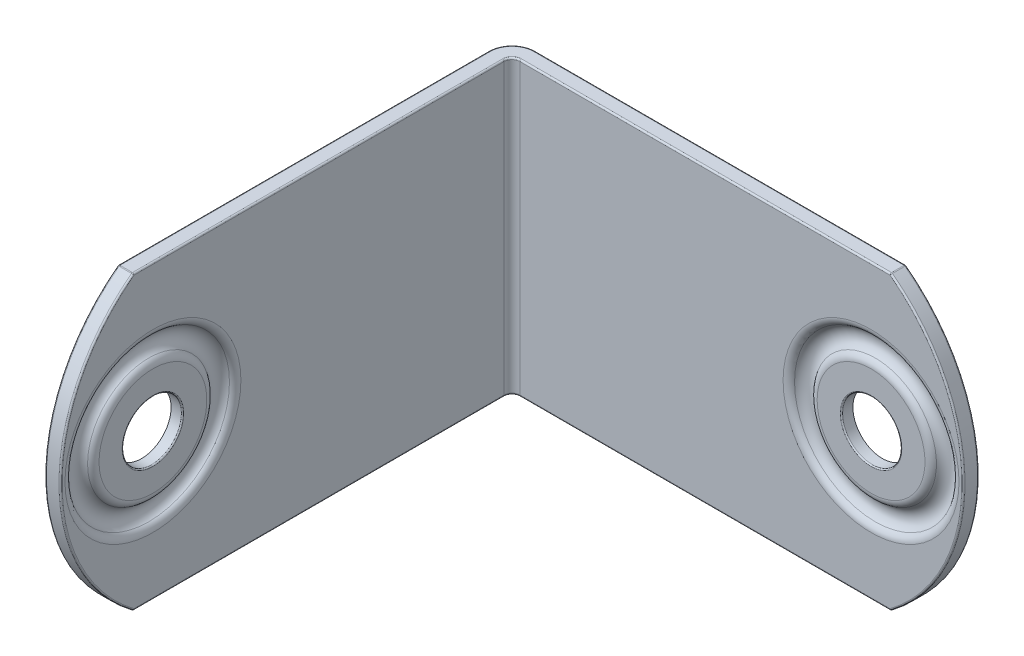
SolidWorks part; units mm, degrees
ref_plane "Front Plane" through (0, 0, 0) normal (0, 0, 1) x (1, 0, 0)
ref_plane "Top Plane" through (0, 0, 0) normal (0, 1, 0) x (1, 0, 0)
ref_plane "Right Plane" through (0, 0, 0) normal (1, 0, 0) x (0, 0, -1)
sketch "Sketch1" plane through (0, 0, 0) normal (0, 1, 0) x (1, 0, 0)
  line L0 (-19.05, -19.05) -> (-19.05, 19.05)
  line L1 (-19.05, 19.05) -> (19.05, 19.05)
  line L2 (-19.05, -19.05) -> (-17.78, -19.05)
  line L3 (-17.78, -19.05) -> (-17.78, 17.78)
  line L4 (-17.78, 17.78) -> (19.05, 17.78)
  line L5 (19.05, 17.78) -> (19.05, 19.05)
  line L6 (11.5094, 19.05) -> (11.5094, 17.78) construction
  line L7 (-19.05, -11.5094) -> (-17.78, -11.5094) construction
  line L8 (13.9224, 19.05) -> (13.9224, 17.78)
  line L9 (-19.05, -9.0964) -> (-17.78, -9.0964)
  line L10 (-19.05, -13.9224) -> (-17.78, -13.9224)
  line L11 (9.0964, 19.05) -> (9.0964, 17.78)
  arc A0 (-19.05, 17.145) -> (-17.145, 19.05) centre (-17.145, 17.145) cw
  arc A1 (-17.78, 17.145) -> (-17.145, 17.78) centre (-17.145, 17.145) cw
  point P2 (-19.05, 0)
  point P5 (0, 19.05)
  point P27 (-17.78, -13.9224)
  point P29 (9.0964, 17.78)
  dimension "D1" = 0.635
  dimension "Length (B)" = 38.1
  dimension "Length (A)" = 38.1
  dimension "Thickness" = 1.27
  dimension "Mounting Hole Location 2" = 7.5406
  dimension "Mounting Hole Location 1" = 7.5406
  dimension "Mounting Hole Diameter 2" = 4.826
  dimension "Mounting Hole Diameter 1" = 4.826
sketch "Sketch2" plane through (0, 0, 0) normal (1, 0, 0) x (0, 0, -1)
  line L0 (0, 11.9062) -> (0, -11.9062)
  arc A0 (-13.0969, 11.9062) -> (-13.0969, -11.9062) centre (-4.1672, 0) ccw
  point P2 (0, 0)
  point P10 (-19.05, 0)
  dimension "Length (C)" = 23.8125
  dimension "D1" = 5.9531
sketch "Sketch3" plane through (0, 0, 0) normal (0, 1, 0) x (1, 0, 0)
  line L0 (-19.05, -19.05) -> (-17.78, -19.05) construction
  line L1 (-17.78, -19.05) -> (-17.78, 17.78) construction
  line L2 (-17.78, 17.78) -> (19.05, 17.78) construction
  line L3 (19.05, 17.78) -> (19.05, 19.05) construction
  line L4 (-19.05, 19.05) -> (19.05, 19.05) construction
  line L5 (-19.05, -19.05) -> (-19.05, 19.05) construction
  line L6 (-19.05, -19.05) -> (-17.78, -19.05)
  line L7 (-17.78, -19.05) -> (-17.78, 17.145)
  line L8 (-17.145, 17.78) -> (19.05, 17.78)
  line L9 (19.05, 17.78) -> (19.05, 19.05)
  line L10 (-17.145, 19.05) -> (19.05, 19.05)
  line L11 (-19.05, -19.05) -> (-19.05, 17.145)
  arc A0 (-17.145, 17.78) -> (-17.78, 17.145) centre (-17.145, 17.145) ccw construction
  arc A1 (-17.145, 19.05) -> (-19.05, 17.145) centre (-17.145, 17.145) ccw construction
  arc A2 (-17.145, 17.78) -> (-17.78, 17.145) centre (-17.145, 17.145) ccw
  arc A3 (-17.145, 19.05) -> (-19.05, 17.145) centre (-17.145, 17.145) ccw
extrude "Boss-Extrude1" add sketch "Sketch3" against normal up to vertex (11.9062 mm away) from vertex at 11.9062 starting at point (0, 11.9062, 0)
sketch "Sketch4" plane through (0, 0, 0) normal (0, 1, 0) x (1, 0, 0)
  line L1 (-19.05, -11.5094) -> (-17.78, -11.5094)
  line L2 (-19.05, -11.5094) -> (-19.05, -9.0964)
  line L3 (-19.05, -9.0964) -> (-17.78, -9.0964)
  line L4 (-17.78, -11.5094) -> (-17.78, -9.0964)
revolve "Cut-Revolve1" cut sketch "Sketch4" angle 360 about L1
sketch "Sketch5" plane through (0, 0, 0) normal (0, 1, 0) x (1, 0, 0)
  line L1 (11.5094, 19.05) -> (13.9224, 19.05)
  line L2 (11.5094, 19.05) -> (11.5094, 17.78)
  line L3 (11.5094, 17.78) -> (13.9224, 17.78)
  line L4 (13.9224, 19.05) -> (13.9224, 17.78)
revolve "Cut-Revolve2" cut sketch "Sketch5" angle 360 about L2
sketch "Sketch6" plane through (-17.78, 0, 0) normal (1, 0, 0) x (0, 0, -1)
  line L0 (-13.0969, 11.9063) -> (-19.05, 11.9062)
  line L1 (-19.05, 11.9062) -> (-19.05, 0)
  line L2 (-19.05, 0) -> (-19.05, -11.9062)
  line L3 (-19.05, -11.9062) -> (-13.0969, -11.9063)
  arc A0 (-13.0969, 11.9063) -> (-13.0969, -11.9063) centre (-4.1672, 0) ccw construction
  arc A1 (-13.0969, 11.9063) -> (-13.0969, -11.9063) centre (-4.1672, 0) ccw
  line M2 (17.145, 11.9062) -> (-19.05, 11.9062)
  line M3 (-19.05, 11.9062) -> (-19.05, -11.9062)
  line M4 (-19.05, -11.9062) -> (17.145, -11.9062)
extrude "Cut-Extrude1" cut sketch "Sketch6" against normal through all contours A1 M2 M3 | A1 M3 M4
sketch "Sketch7" plane through (0, 0, -17.78) normal (0, 0, 1) x (1, 0, 0)
  line L0 (-17.145, 11.9062) -> (19.05, 11.9062) construction
  line L1 (-17.145, -11.9062) -> (19.05, -11.9062) construction
  line L3 (13.0969, 11.9062) -> (19.05, 11.9062)
  line L4 (19.05, 11.9062) -> (19.05, 0)
  line L5 (19.05, 0) -> (19.05, -11.9062)
  line L6 (19.05, -11.9062) -> (13.0969, -11.9062)
  arc A0 (13.0969, 11.9062) -> (13.0969, -11.9062) centre (4.1672, 0) cw
  line M2 (19.05, 11.9062) -> (-17.145, 11.9062)
  line M4 (-17.145, -11.9062) -> (19.05, -11.9062)
  line M5 (19.05, -11.9062) -> (19.05, 11.9062)
  dimension "D1" = 5.9531
extrude "Cut-Extrude2" cut sketch "Sketch7" against normal through all contours A0 M2 M5 | A0 M5 M4
fillet "Fillet1" radius 0.127 20 edges at (-19.05, -11.9062, -2.0241) (-18.492, -11.9062, -18.492) (-19.05, 11.9062, -2.0241) (-18.492, 11.9062, -18.492) (-2.0241, -11.9062, -17.78) (-17.594, -11.9062, -17.594) (-2.0241, 11.9062, -17.78) (-17.594, 11.9062, -17.594) (-18.415, -11.9062, 13.0969) (13.0969, -11.9062, -18.415) (13.0969, 11.9062, -18.415) (-18.415, 11.9062, 13.0969) (-2.0241, -11.9062, -19.05) (-2.0241, 11.9062, -19.05) (19.05, 0, -19.05) (19.05, 0, -17.78) (-17.78, -11.9062, -2.0241) (-17.78, 11.9062, -2.0241) (-19.05, 0, 19.05) (-17.78, 0, 19.05)
fillet "Fillet2" radius 0.0965 4 edges at (9.0964, 0, -19.05) (-19.05, 0, 13.9224) (9.0964, 0, -17.78) (-17.78, 0, 13.9224)
sketch "Sketch8" plane through (0, 0, 0) normal (0, 1, 0) x (1, 0, 0)
  line L0 (-17.78, -4.3339) -> (-17.78, -7.112)
  line L1 (-17.78, -19.05) -> (-17.78, 17.78) construction
  line L2 (-19.05, -19.05) -> (-19.05, 19.05) construction
  line L3 (-18.7098, -7.112) -> (-18.7098, -9.0964)
  line L4 (-17.78, -7.112) -> (-17.78, -8.9999) construction
  line L6 (-18.7098, -9.0964) -> (-19.05, -9.0964)
  line L8 (-19.05, -9.0964) -> (-17.78, -9.0964) construction
  line L9 (-19.05, -9.0964) -> (-19.05, -6.5167)
  arc A0 (-17.78, -7.112) -> (-18.1202, -6.5167) centre (-18.471, -7.112) ccw
  arc A1 (-18.1202, -6.5167) -> (-18.1202, -4.9292) centre (-17.6524, -5.7229) cw
  arc A2 (-18.1202, -4.9292) -> (-17.78, -4.3339) centre (-18.471, -4.3339) ccw
  arc A3 (-18.7098, -7.112) -> (-19.05, -6.5167) centre (-19.4008, -7.112) ccw
  arc A4 (-19.05, -6.5167) -> (-19.05, -4.9292) centre (-18.5823, -5.7229) cw construction
  arc A5 (-19.05, -4.9292) -> (-18.7098, -4.3339) centre (-19.4008, -4.3339) ccw construction
  point P21 (-19.5036, -5.7229)
  point P22 (-18.5738, -5.7229)
  dimension "D1" = 0.7937
  dimension "D2" = 1.9844
  dimension "D3" = 2.7781
  dimension "D4" = 0.7937
  dimension "D5" = 1.5875
revolve "Cut-Revolve3" cut sketch "Sketch8" angle 360 about L7
sketch "Sketch9" plane through (0, 0, 0) normal (0, 1, 0) x (1, 0, 0)
  line L0 (-19.05, -4.9292) -> (-19.05, -6.5167)
  arc A0 (-19.05, -4.9292) -> (-19.05, -6.5167) centre (-18.5823, -5.7229) ccw construction
  arc A1 (-19.05, -4.9292) -> (-19.05, -6.5167) centre (-18.5823, -5.7229) ccw
revolve "Revolve1" add sketch "Sketch9" angle 360 about L7
sketch "Sketch10" plane through (0, 0, 0) normal (0, 1, 0) x (1, 0, 0)
  line L0 (18.6849, 17.78) -> (15.9068, 17.78)
  line L1 (15.9068, 18.7098) -> (13.9224, 18.7098)
  line L2 (15.9068, 17.78) -> (13.9224, 17.78) construction
  line L3 (13.9224, 18.7098) -> (13.9224, 19.05)
  line L4 (13.9224, 19.05) -> (16.5021, 19.05)
  line L5 (-19.05, 19.05) -> (19.05, 19.05) construction
  line L6 (13.9224, 19.05) -> (13.9224, 17.78) construction
  arc A0 (15.9068, 17.78) -> (16.5021, 18.1202) centre (15.9068, 18.471) ccw
  arc A1 (16.5021, 18.1202) -> (18.0896, 18.1202) centre (17.2958, 17.6524) cw
  arc A2 (18.0896, 18.1202) -> (18.6849, 17.78) centre (18.6849, 18.471) ccw
  arc A3 (15.9068, 18.7098) -> (16.5021, 19.05) centre (15.9068, 19.4008) ccw
  arc A4 (16.5021, 19.05) -> (18.0896, 19.05) centre (17.2958, 18.5823) cw construction
  arc A5 (18.0896, 19.05) -> (18.6849, 18.7098) centre (18.6849, 19.4008) ccw construction
  point P15 (17.2958, 19.5036)
  point P16 (17.2958, 18.5738)
  dimension "D1" = 2.7781
  dimension "D2" = 1.5875
  dimension "D3" = 0.7937
  dimension "D4" = 0.7938
  dimension "D5" = 1.9844
revolve "Cut-Revolve4" cut sketch "Sketch10" angle 360 about L6
sketch "Sketch11" plane through (0, 0, 0) normal (0, 1, 0) x (1, 0, 0)
  line L0 (16.5021, 19.05) -> (18.0896, 19.05)
  arc A0 (18.0896, 19.05) -> (16.5021, 19.05) centre (17.2958, 18.5823) ccw construction
  arc A1 (18.0896, 19.05) -> (16.5021, 19.05) centre (17.2958, 18.5823) ccw
revolve "Revolve2" add sketch "Sketch11" angle 360 about L6
equation "\"D1@Sketch1\"=\"Thickness@Sketch1\"*0.5"
equation "\"D1@Sketch2\"=\"Length (C)@Sketch2\"*0.25"
equation "\"D1@Sketch7\" = \"D1@Sketch2\""
equation "\"D1@Fillet1\"=0.1*\"Thickness@Sketch1\""
equation "\"D1@Fillet2\"=\"Mounting Hole Diameter 2@Sketch1\"*.02"
